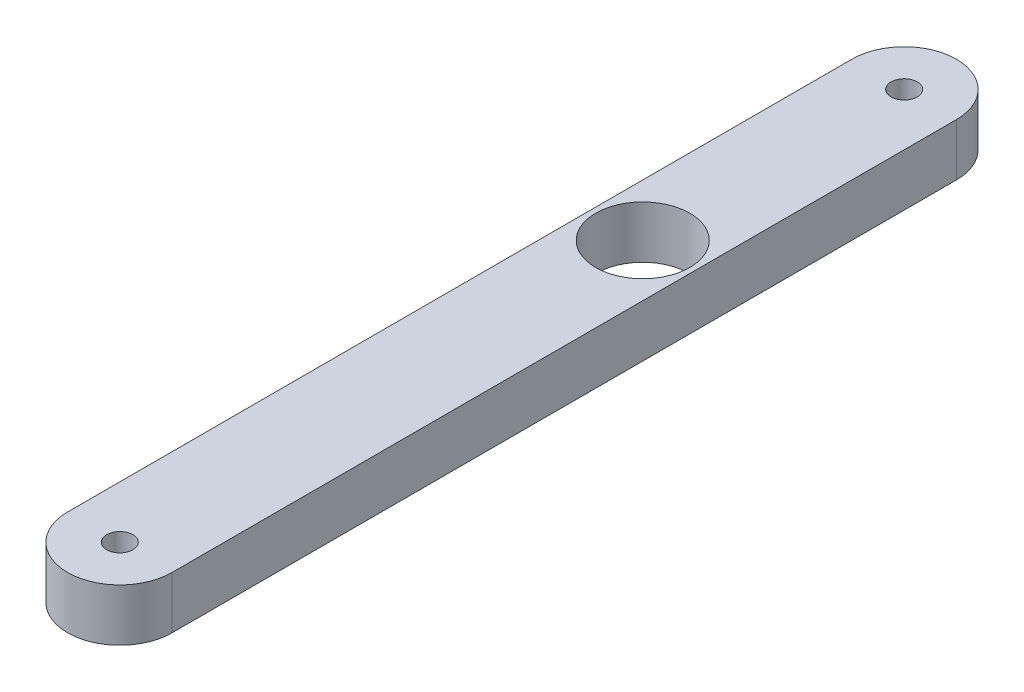
SolidWorks part; units mm, degrees
ref_plane "Front Plane" through (0, 0, 0) normal (0, 0, 1) x (1, 0, 0)
ref_plane "Top Plane" through (0, 0, 0) normal (0, 1, 0) x (1, 0, 0)
ref_plane "Right Plane" through (0, 0, 0) normal (1, 0, 0) x (0, 0, -1)
sketch "Sketch1" plane through (0, 0, 0) normal (0, 1, 0) x (1, 0, 0)
  line L0 (0, 0) -> (49.1133, 0) construction
  line L1 (-10, -75) -> (10, -75)
  line L2 (-10, -75) -> (-10, 75)
  line L3 (-10, 75) -> (10, 75)
  line L4 (10, -75) -> (10, 75)
  line L5 (-10, -75) -> (10, 75) construction
  line L6 (-10, 75) -> (10, -75) construction
  arc A0 (10, 75) -> (-10, 75) centre (0, 75) ccw
  circle A1 centre (0, 75) radius 4 construction
  circle A2 centre (0, 75) radius 2.5
  arc A3 (10, -75) -> (-10, -75) centre (0, -75) cw
  circle A4 centre (0, -75) radius 4 construction
  circle A5 centre (0, -75) radius 2.5
  point P0 (0, 0)
  dimension "D4" = 8
  dimension "D3" = 150
  dimension "D2" = 7.5
  dimension "D5" = 5
extrude "Boss-Extrude1" add sketch "Sketch1" along normal blind 10 contours A2 L3 L2 L1 L4 | A2 L3 A0 | L1 A5 A3
sketch "Sketch2" plane through (0, 10, 0) normal (0, 1, 0) x (1, 0, 0)
  circle A1 centre (0, 25) radius 9
  circle A2 centre (0, 25) radius 11
  circle A3 centre (0, 75) radius 2.5 construction
  dimension "D1" = 18
  dimension "D2" = 2
  dimension "D3" = 50
extrude "MotorMountBore" cut sketch "Sketch2" against normal through all contours A1
